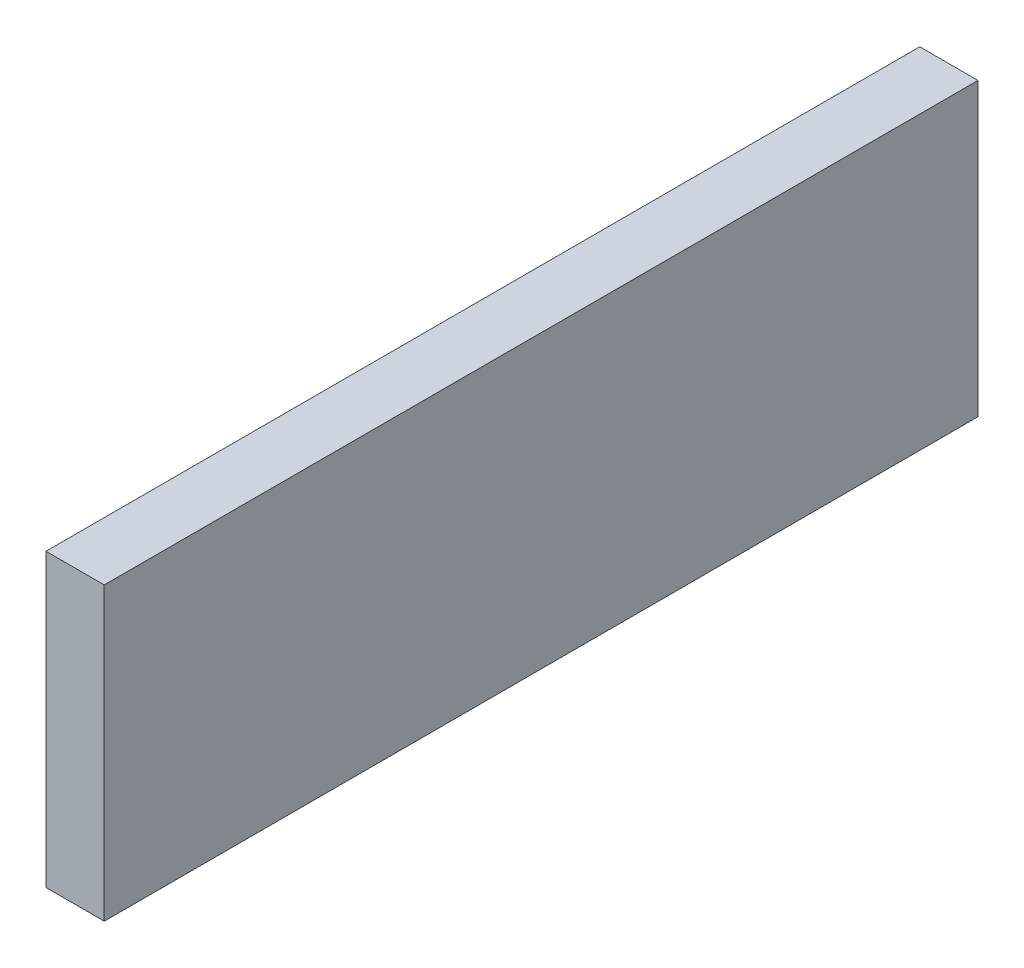
SolidWorks part; units mm, degrees
ref_plane "前视基准面" through (0, 0, 0) normal (0, 0, 1) x (1, 0, 0)
ref_plane "上视基准面" through (0, 0, 0) normal (0, 1, 0) x (1, 0, 0)
ref_plane "右视基准面" through (0, 0, 0) normal (1, 0, 0) x (0, 0, -1)
sketch "草图1" plane through (0, 0, 0) normal (0, 1, 0) x (1, 0, 0)
  line L1 (0, 0) -> (20, 0)
  line L2 (0, 0) -> (0, -300)
  line L3 (0, -300) -> (20, -300)
  line L4 (20, 0) -> (20, -300)
  dimension "D1" = 20
  dimension "D2" = 300
extrude "凸台-拉伸1" add sketch "草图1" along normal blind 100
